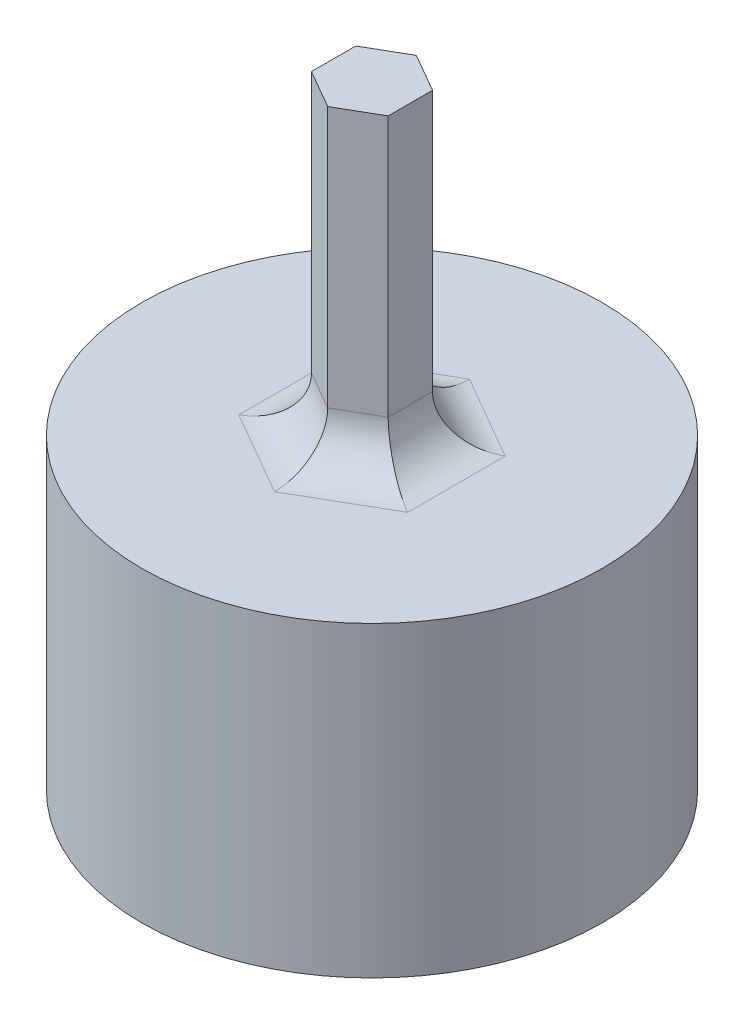
SolidWorks part; units mm, degrees
ref_plane "Front Plane" through (0, 0, 0) normal (0, 0, 1) x (1, 0, 0)
ref_plane "Top Plane" through (0, 0, 0) normal (0, 1, 0) x (1, 0, 0)
ref_plane "Right Plane" through (0, 0, 0) normal (1, 0, 0) x (0, 0, -1)
sketch "Sketch1" plane through (0, 0, 0) normal (0, 1, 0) x (1, 0, 0)
  line L1 (-7.5, 7.5) -> (7.5, 7.5)
  line L2 (-7.5, 7.5) -> (-7.5, -7.5)
  line L3 (-7.5, -7.5) -> (7.5, -7.5)
  line L4 (7.5, 7.5) -> (7.5, -7.5)
  line L5 (-7.5, 7.5) -> (7.5, -7.5) construction
  line L6 (-7.5, -7.5) -> (7.5, 7.5) construction
  circle A0 centre (0, 0) radius 15
  dimension "D1" = 30
  dimension "D2" = 15
  dimension "D3" = 15
extrude "Boss-Extrude1" add sketch "Sketch1" along normal blind 15
sketch "Sketch2" plane through (0, 15, 0) normal (0, 1, 0) x (1, 0, 0)
  circle A0 centre (0, 0) radius 15
  dimension "D1" = 30
extrude "Boss-Extrude2" add sketch "Sketch2" along normal blind 5
sketch "Sketch3" plane through (0, 20, 0) normal (0, 1, 0) x (1, 0, 0)
  line L0 (0, 15) -> (0, -15) construction
  line L1 (2.5, -1.4434) -> (2.5, 1.4434)
  line L2 (2.5, 1.4434) -> (0, 2.8868)
  line L3 (0, 2.8868) -> (-2.5, 1.4434)
  line L4 (-2.5, 1.4434) -> (-2.5, -1.4434)
  line L5 (-2.5, -1.4434) -> (0, -2.8868)
  line L6 (0, -2.8868) -> (2.5, -1.4434)
  circle A0 centre (0, 0) radius 2.5 construction
  circle A1 centre (0, 0) radius 15 construction
  point P1 (0, 0)
  point P15 (0, 0)
  dimension "D1" = 5
extrude "Boss-Extrude3" add sketch "Sketch3" along normal blind 20 contours L2 L3 L4 L5 L6 L1
fillet "Fillet1" radius 3 6 edges at (-1.25, 20, -2.1651) (1.25, 20, -2.1651) (2.5, 20, 0) (1.25, 20, 2.1651) (-1.25, 20, 2.1651) (-2.5, 20, 0)
